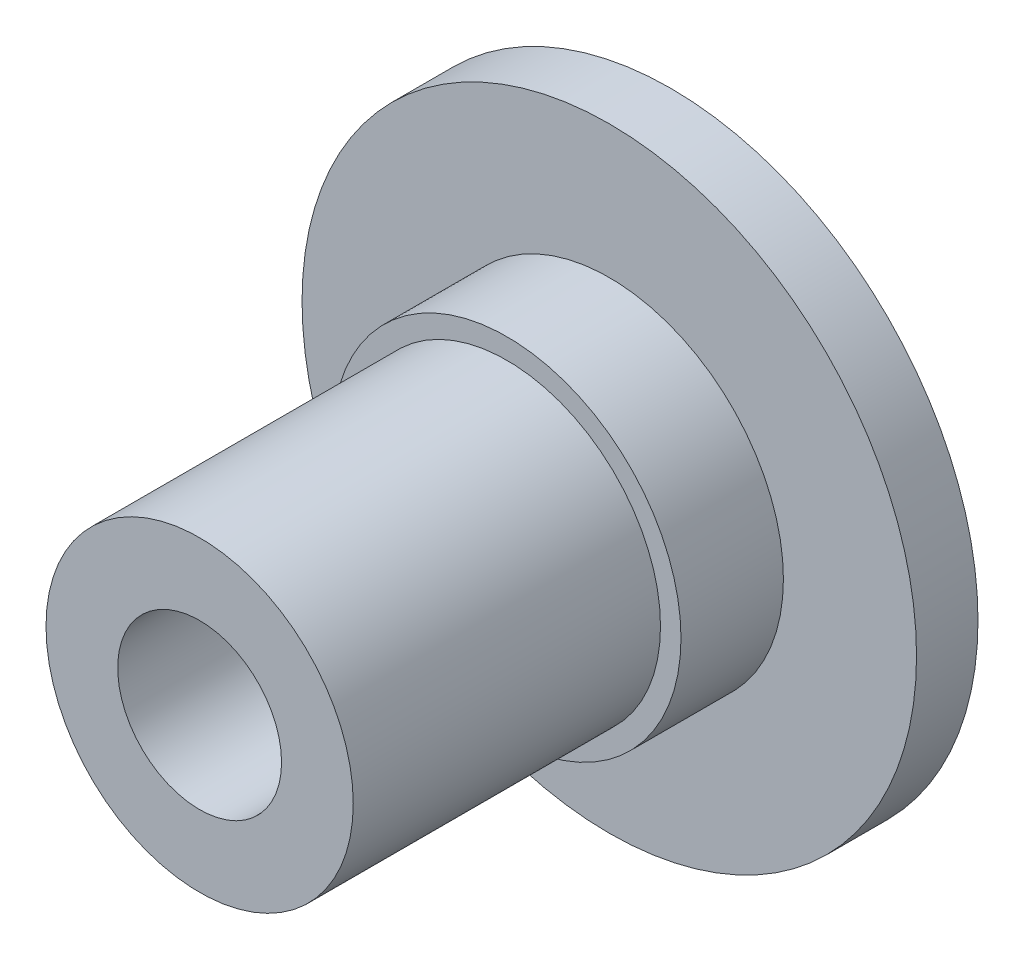
SolidWorks part; units mm, degrees
ref_plane "Спереди" through (0, 0, 0) normal (0, 0, 1) x (1, 0, 0)
ref_plane "Сверху" through (0, 0, 0) normal (0, 1, 0) x (1, 0, 0)
ref_plane "Справа" through (0, 0, 0) normal (1, 0, 0) x (0, 0, -1)
sketch "Эскиз1" plane through (0, 0, 0) normal (0, 0, 1) x (1, 0, 0)
  circle A0 centre (0, 0) radius 15
  dimension "D1" = 30
extrude "Бобышка-Вытянуть1" add sketch "Эскиз1" along normal blind 3
sketch "Эскиз2" plane through (0, 0, 3) normal (0, 0, 1) x (1, 0, 0)
  circle A0 centre (0, 0) radius 8.5
  dimension "D1" = 17
extrude "Бобышка-Вытянуть2" add sketch "Эскиз2" along normal blind 20
sketch "Эскиз3" plane through (0, 0, 23) normal (0, 0, 1) x (1, 0, 0)
  circle A0 centre (0, 0) radius 7.5
  circle A1 centre (0, 0) radius 10.3329
  dimension "D1" = 15
extrude "Вырез-Вытянуть1" cut sketch "Эскиз3" against normal blind 15
sketch "Эскиз4" plane through (0, 0, 23) normal (0, 0, 1) x (1, 0, 0)
  circle A0 centre (0, 0) radius 4
  dimension "D1" = 8
extrude "Вырез-Вытянуть2" cut sketch "Эскиз4" against normal blind 37
chamfer "Фаска1" distance 2.8 angle 45 1 edges at (4, 0, 0)
